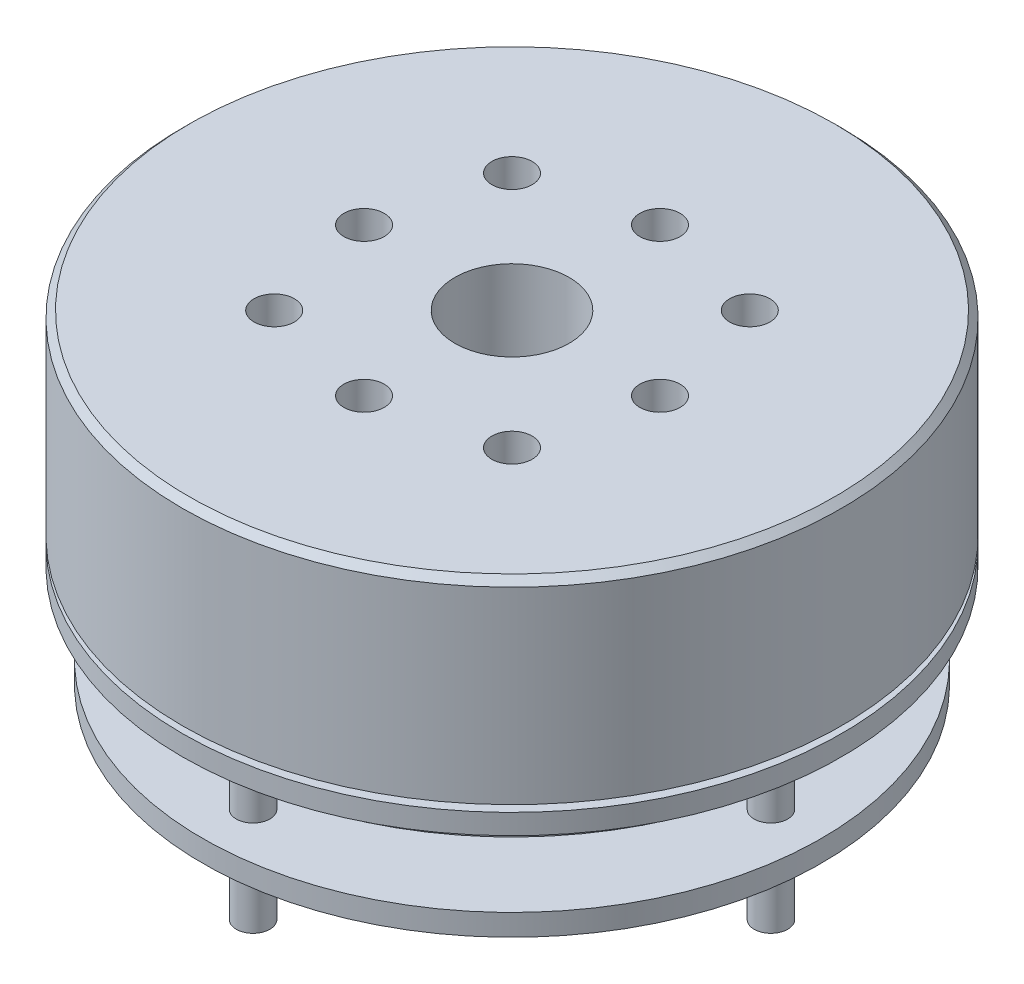
SolidWorks part; units mm, degrees
ref_plane "前视基准面" through (0, 0, 0) normal (0, 0, 1) x (1, 0, 0)
ref_plane "上视基准面" through (0, 0, 0) normal (0, 1, 0) x (1, 0, 0)
ref_plane "右视基准面" through (0, 0, 0) normal (1, 0, 0) x (0, 0, -1)
sketch "草图1" plane through (0, 0, 0) normal (0, 0, 1) x (1, 0, 0)
  line L1 (24, 22.1) -> (0, 22.1)
  line L4 (24.5, 21.6) -> (24.5, 7.6)
  line L6 (24.5, 7.6) -> (23.5, 7.6)
  line L7 (23.5, 7.6) -> (23.5, 7.1)
  line L8 (23.5, 7.1) -> (24.5, 7.1)
  line L9 (24.5, 7.1) -> (24.5, 5.6)
  line L10 (24.5, 21.6) -> (24, 22.1)
  line L12 (24.5, 5.6) -> (22.5, 5.6)
  line L13 (22.5, 5.6) -> (22.5, 4.1)
  line L14 (22.5, 4.1) -> (8.3, 4.1)
  line L17 (0, 4.5453) -> (0, 22.1)
  line L22 (0, 4.5453) -> (0, 3.1)
  line L23 (0, 3.1) -> (8.3, 3.1)
  line L24 (8.3, 3.1) -> (8.3, 4.1)
  point P0 (0, 0)
revolve "旋转1" add sketch "草图1" angle 360 about L17
sketch "草图2" plane through (0, 22.1, 0) normal (0, 1, 0) x (1, 0, 0)
  line L0 (0, 0) -> (0, 25.9186) construction
  circle A0 centre (0, 0) radius 11 construction
  circle A1 centre (0, 11) radius 1.5
  circle A2 centre (11, 0) radius 1.5
  circle A3 centre (0, -11) radius 1.5
  circle A4 centre (-11, 0) radius 1.5
  circle A5 centre (0, 0) radius 12.5 construction
  circle A8 centre (8.8388, 8.8388) radius 1.5
  circle A10 centre (8.8388, -8.8388) radius 1.5
  circle A12 centre (-8.8388, -8.8388) radius 1.5
  circle A14 centre (-8.8388, 8.8388) radius 1.5
  point P15 (0, 0)
  point P33 (0, 0)
  dimension "D1" = 4
extrude "切除-拉伸1" cut sketch "草图2" against normal blind 3
sketch "草图3" plane through (0, 22.1, 0) normal (0, 1, 0) x (1, 0, 0)
  circle A0 centre (0, 0) radius 4.25
extrude "切除-拉伸2" cut sketch "草图3" against normal blind 18
sketch "草图5" plane through (0, 4.1, 0) normal (0, -1, 0) x (1, 0, 0)
  line L0 (0, 0) -> (0, 24.6178) construction
  circle A0 centre (0, 0) radius 12.5 construction
  circle A2 centre (0, 12.5) radius 1
  circle A4 centre (12.5, 0) radius 1
  circle A5 centre (0, -12.5) radius 1
  circle A6 centre (-12.5, 0) radius 1
  point P17 (0, 0)
  dimension "D1" = 4
sketch "草图6" plane through (0, 4.1, 0) normal (0, -1, 0) x (1, 0, 0)
  circle A0 centre (0, 0) radius 19.25 construction
  circle A1 centre (0, 19.25) radius 1.25
  circle A2 centre (19.25, 0) radius 1.25
  circle A3 centre (0, -19.25) radius 1.25
  circle A4 centre (-19.25, 0) radius 1.25
  point P14 (0, 0)
  dimension "D1" = 4
extrude "凸台-拉伸1" add sketch "草图6" along normal blind 4.5
sketch "草图7" plane through (0, -0.4, 0) normal (0, -1, 0) x (1, 0, 0)
  circle A0 centre (0, 0) radius 23
extrude "凸台-拉伸2" add sketch "草图7" along normal blind 1.6
sketch "草图10" plane through (0, -2, 0) normal (0, -1, 0) x (1, 0, 0)
  circle A0 centre (0, 0) radius 19.25 construction
  circle A1 centre (0, 19.25) radius 1.25
  circle A2 centre (19.25, 0) radius 1.25
  circle A3 centre (0, -19.25) radius 1.25
  circle A4 centre (-19.25, 0) radius 1.25
  point P14 (0, 0)
  dimension "D1" = 4
extrude "凸台-拉伸3" add sketch "草图10" along normal blind 5.5
